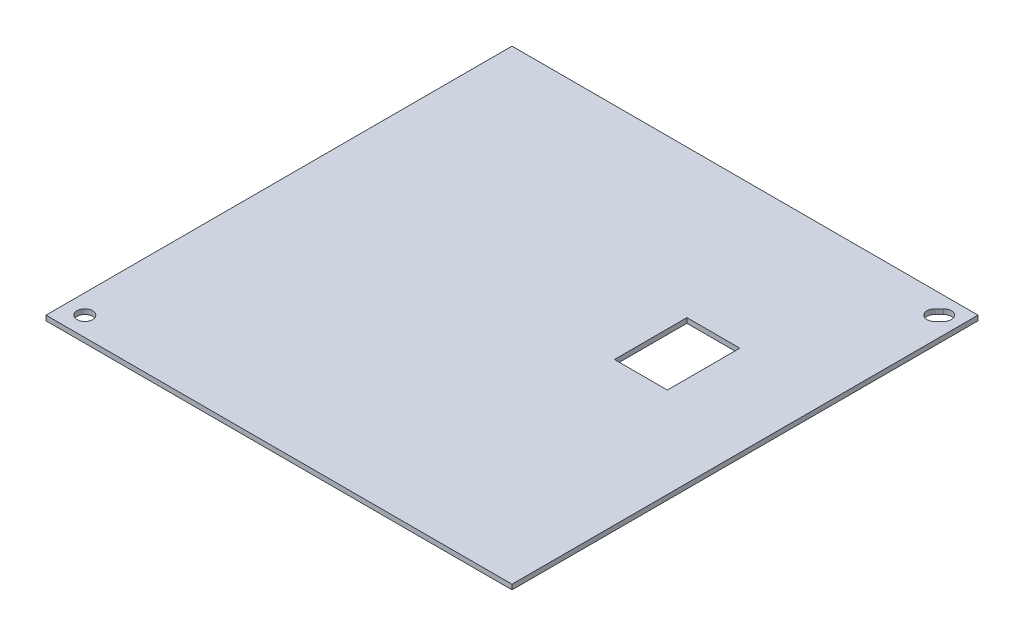
SolidWorks part; units mm, degrees
material "Acrylic (Medium-high impact)"
ref_plane "Front Plane" through (0, 0, 0) normal (0, 0, 1) x (1, 0, 0)
ref_plane "Top Plane" through (0, 0, 0) normal (0, 1, 0) x (1, 0, 0)
ref_plane "Right Plane" through (0, 0, 0) normal (1, 0, 0) x (0, 0, -1)
sketch "Sketch1" plane through (0, 0, 0) normal (0, 1, 0) x (1, 0, 0)
  line L1 (-150, -150) -> (150, -150)
  line L2 (-150, -150) -> (-150, 150)
  line L3 (-150, 150) -> (150, 150)
  line L4 (150, -150) -> (150, 150)
  line L5 (-150, -150) -> (150, 150) construction
  line L6 (-150, 150) -> (150, -150) construction
  point P0 (0, 0)
  dimension "D1" = 300
  dimension "D2" = 300
extrude "Boss-Extrude1" add sketch "Sketch1" along normal blind 3.175
sketch "Sketch2" plane through (0, 3.175, 0) normal (0, 1, 0) x (1, 0, 0)
  line L0 (138.9142, 138.9142) -> (136.0858, 136.0858) construction
  line L1 (142.4497, 135.3787) -> (139.6213, 132.5503)
  line L2 (135.3787, 142.4497) -> (132.5503, 139.6213)
  line L3 (-150, 150) -> (-150, -150) construction
  line L4 (-150, -150) -> (150, -150) construction
  line L5 (150, -150) -> (150, 150) construction
  line L6 (150, 150) -> (-150, 150) construction
  circle A0 centre (-137.5, -137.5) radius 5
  arc A1 (142.4497, 135.3787) -> (135.3787, 142.4497) centre (138.9142, 138.9142) ccw
  arc A2 (132.5503, 139.6213) -> (139.6213, 132.5503) centre (136.0858, 136.0858) ccw
  point P4 (137.5, 137.5)
  dimension "D2" = 10
  dimension "D7" = 5
  dimension "D1" = 12.5
  dimension "D3" = 12.5
  dimension "D4" = 12.5
  dimension "D5" = 12.5
  dimension "D6" = 4
extrude "Cut-Extrude1" cut sketch "Sketch2" against normal through all
sketch "Sketch3" plane through (0, 3.175, 0) normal (0, 1, 0) x (1, 0, 0)
  line L1 (57.686, 8.2571) -> (91.746, 8.2571)
  line L2 (57.686, 8.2571) -> (57.686, 54.9271)
  line L3 (57.686, 54.9271) -> (91.746, 54.9271)
  line L4 (91.746, 8.2571) -> (91.746, 54.9271)
  line L5 (57.686, 8.2571) -> (91.746, 54.9271) construction
  line L6 (57.686, 54.9271) -> (91.746, 8.2571) construction
  point P0 (74.716, 31.5921)
  dimension "D1" = 46.67
  dimension "D2" = 34.06
extrude "Cut-Extrude2" cut sketch "Sketch3" against normal through all
